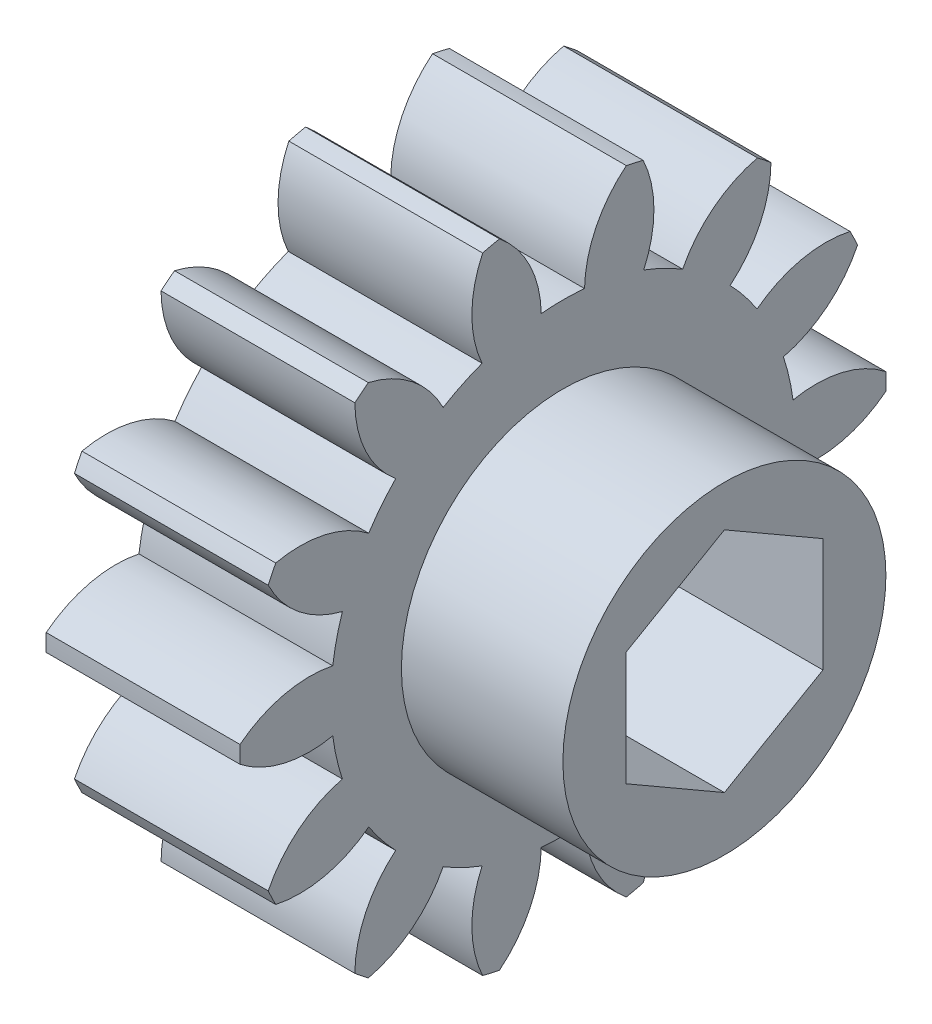
SolidWorks part; units mm, degrees
material "PLA "
ref_plane "Plane1" through (0, 0, 0) normal (0, 0, 1) x (1, 0, 0)
ref_plane "Plane2" through (0, 0, 0) normal (0, 1, 0) x (1, 0, 0)
ref_plane "Plane3" through (0, 0, 0) normal (1, 0, 0) x (0, 0, -1)
sketch "HoldingSke" plane through (0, 0, 0) normal (0, 1, 0) x (1, 0, 0)
  line L0 (0, 0) -> (0.3881, -0.0968)
  line L1 (-15, 0) -> (100, 0) construction
  line L2 (0, 0) -> (-2.1039, 2.3779)
  line L3 (0, 0) -> (-11.863, 4.5341)
  line L4 (0, 0) -> (8.3795, 2.0892)
  line L5 (0, 0) -> (-46.8476, -17.4728)
  line L6 (0, 0) -> (-9.9476, -6.7116)
  line L7 (-2.1039, 2.3779) -> (8.6586, 51.2059)
  line L8 (-76.2, 54.61) -> (-76.1, 54.61)
  line L9 (-71.009, 38.7566) -> (-53.1078, 45.2721)
  line L10 (-76.2, 71.12) -> (104.1128, 71.12)
  line L11 (0, 0) -> (-12, 0)
  line L12 (-76.2, 101.6) -> (-76.113, 101.6)
  line L13 (24.9733, 27.94) -> (52.9518, 28.4284)
  line L14 (24.9733, 27.94) -> (24.9743, 27.94)
  line L15 (24.9733, 27.94) -> (100.4006, 29.5858)
  line L16 (-63.627, -2.5) -> (-12.827, -2.5)
  circle A0 centre (0, 0) radius 0.4
  circle A1 centre (0, 0) radius 14.374
  circle A2 centre (0, 0) radius 37.5
  circle A3 centre (0, 0) radius 0.4
  dimension "MHD" = 28.748
  dimension "Hub_dia" = 75
  dimension "Bore" = 0.8
  dimension "MBD" = 0.8
  dimension "Num_teeth" = 14
  dimension "Pitch" = 0.4
  dimension "Overall_len" = 50
  dimension "Show_teeth" = 14
  dimension "Thickness" = 12
  dimension "OAL" = 50.0001
  dimension "T_dim" = 0.1
  dimension "Ap" = 20
  dimension "H" = 19.05
  dimension "Pitch_radius" = 180.3128
  dimension "Width" = 12
  dimension "Backlash" = 0.087
  dimension "Addendum_fac" = 1
  dimension "Dedendum_fac" = 1.25
  dimension "Clearance_fac" = 0.25
  dimension "Dedendum_add" = 0.001
  dimension "Module" = 2.5
sketch "BasProSke" plane through (0, 0, 0) normal (0, 1, 0) x (1, 0, 0)
  line L0 (-10, 0) -> (60, 0) construction
  line L1 (0, 0) -> (0, 20)
  line L2 (0, 0) -> (12, 0)
  line L3 (12, 0) -> (12, 20)
  line L4 (12, 20) -> (0, 20)
  dimension "Thickness" = 12
  dimension "Diameter" = 40
revolve "Base-Revolve" add sketch "BasProSke" angle 360 about L0
sketch "TooCutSke" plane through (0, 0, 0) normal (1, 0, 0) x (0, 0, -1)
  line L1 (0, 0) -> (0, 107) construction
  line L2 (0, 0) -> (-2.1115, 17.3722) construction
  line L3 (0, 0) -> (-7.7466, 33.9401) construction
  line L4 (-2.1115, 17.3722) -> (-3.8733, 16.97) construction
  arc A0 (1.3395, 14.3115) -> (-1.3395, 14.3115) centre (0, 0) ccw
  arc A1 (3.9542, 19.6311) -> (-3.9542, 19.6311) centre (0, 0) ccw
  circle A2 centre (0, 0) radius 17.5 construction
  circle A3 centre (0, 0) radius 16.4446 construction
  arc A4 (-1.3395, 14.3115) -> (-3.9542, 19.6311) centre (-8.3382, 14.1739) ccw
  arc A5 (3.9542, 19.6311) -> (1.3395, 14.3115) centre (8.3382, 14.1739) ccw
  dimension "Root_dia" = 28.748
  dimension "Overcut_dia" = 40.0508
  dimension "Pitch_dia" = 35
  dimension "Base_dia" = 32.8892
  dimension "Flank_rad" = 7
  dimension "Half_ang" = 12.857
  dimension "Half_CT" = 1.8071
extrude "ToothCut" cut sketch "TooCutSke" along normal through all
fillet "Breaks" [suppressed] radius 0.05
fillet "RootFillets" [suppressed] radius 0.626
pattern_circular "TeethCuts" count 14 every 25.714 about axis through (-10, 0, 0) along (1, 0, 0) of "ToothCut", "RootFillets", "Breaks"
sketch "HubNeaOneSke" plane through (0, 0, 0) normal (-1, 0, 0) x (0, 0, 1)
  circle A0 centre (0, 0) radius 14.374
  dimension "Diameter" = 28.748
extrude "HubNearOne" [suppressed] add sketch "HubNeaOneSke" along normal blind 38.0001
sketch "HubNeaBotSke" plane through (0, 0, 0) normal (-1, 0, 0) x (0, 0, 1)
  circle A0 centre (0, 0) radius 14.374
  dimension "Diameter" = 28.748
extrude "HubNearBoth" [suppressed] add sketch "HubNeaBotSke" along normal blind 19
ref_plane "FarPln" through (12, 0, 0) normal (1, 0, 0) x (0, 0, -1)
sketch "HubFarSke" plane through (12, 0, 0) normal (1, 0, 0) x (0, 0, -1)
  circle A0 centre (0, 0) radius 14.374
  dimension "Diameter" = 28.748
extrude "HubFar" [suppressed] add sketch "HubFarSke" along normal blind 19
sketch "BorSke" plane through (0, 0, 0) normal (1, 0, 0) x (0, 0, -1)
  circle A0 centre (0, 0) radius 0.4
  dimension "Diameter" = 0.8
extrude "Bore" cut sketch "BorSke" along normal mid plane 100.0001
sketch "KeySke" plane through (0, 0, 0) normal (1, 0, 0) x (0, 0, -1)
  line L0 (-0.05, 0) -> (-0.05, 0.5)
  line L1 (-0.05, 0.5) -> (0.05, 0.5)
  line L2 (0.05, 0.5) -> (0.05, 0)
  line L3 (0, 0) -> (0, 34) construction
  line L4 (-0.05, 0) -> (0.05, 0)
  dimension "Offset" = 0.5
  dimension "Width" = 0.1
extrude "Keyway" [suppressed] cut sketch "KeySke" along normal mid plane 100.0001
pattern_circular "Keyway2" [suppressed] count 2 every 90 about axis through (-10, 0, 0) along (1, 0, 0)
sketch "Sketch1" plane through (12, 0, 0) normal (1, 0, 0) x (0, 0, -1)
  circle A0 centre (0, -0.4) radius 10
  circle A1 centre (0, 0) radius 0.4 construction
  dimension "D1" = 20
extrude "Boss-Extrude1" add sketch "Sketch1" along normal blind 10
sketch "Sketch3" plane through (0, 0, 0) normal (0, 0, 1) x (1, 0, 0)
  line L0 (0, 0) -> (6, 0) construction
  dimension "D1" = 6
sketch "Sketch2" plane through (22, 0, 0) normal (1, 0, 0) x (0, 0, -1)
  line L1 (6.1, 3.5218) -> (0, 7.0437)
  line L2 (0, 7.0437) -> (-6.1, 3.5218)
  line L3 (-6.1, 3.5218) -> (-6.1, -3.5218)
  line L4 (-6.1, -3.5218) -> (0, -7.0437)
  line L5 (0, -7.0437) -> (6.1, -3.5218)
  line L6 (6.1, -3.5218) -> (6.1, 3.5218)
  circle A0 centre (0, 0) radius 6.1 construction
  dimension "D1" = 12.2
extrude "Cut-Extrude1" cut sketch "Sketch2" against normal up to vertex
sketch "Sketch4" [suppressed] plane through (5.9116, 0, 0) normal (1, 0, 0) x (0, 0, -1)
  circle A0 centre (0, 0) radius 2.1
  dimension "D1" = 4.2
extrude "Cut-Extrude2" [suppressed] cut sketch "Sketch4" against normal blind 6
equation "' \"Module@HoldingSke\" = 6.35"
equation "' \"Num_teeth@HoldingSke\" = 12"
equation "' \"Ap@HoldingSke\" =  20"
equation "' \"Ap@HoldingSke\" = 20"
equation "' \"Width@HoldingSke\" = 0.5 * 25.4"
equation "' \"Hub_dia@HoldingSke\"= 1 * 25.4"
equation "' \"Hub_dia@HoldingSke\" = 1 * 25.4"
equation "' \"Overall_len@HoldingSke\" = 1.0 * 25.4"
equation "' \"Bore@HoldingSke\" = 0.75 * 25.4"
equation "' \"T_dim@HoldingSke\" = 0.1 * 25.4"
equation "' \"Width@KeySke\" = 0.25 * 25.4"
equation "' \"Show_teeth@HoldingSke\" = 13"
equation "' \"Backlash@HoldingSke\" = 0.009 * 25.4"
equation "' \"Addendum_fac@HoldingSke\" = 1.0"
equation "' \"Dedendum_fac@HoldingSke\" = 1.25"
equation "' \"Dedendum_add@HoldingSke\" = 0.00005 * 25.4"
equation "' \"Clearance_fac@HoldingSke\" = 0.25"
equation "\"Pitch@HoldingSke\" = 1 / \"Module@HoldingSke\""
equation "\"Overcut_dia@TooCutSke\" = (\"Num_teeth@HoldingSke\" + 2 * \"Addendum_fac@HoldingSke\") / \"Pitch@HoldingSke\" + 0.002 * 25.4"
equation "\"Pitch_dia@TooCutSke\" = \"Num_teeth@HoldingSke\" / \"Pitch@HoldingSke\""
equation "\"Base_dia@TooCutSke\" = \"Num_teeth@HoldingSke\" / \"Pitch@HoldingSke\" * cos((\"Ap@HoldingSke\"  * 3.14159265 / 180))"
equation "\"Root_dia@TooCutSke\" = (\"Num_teeth@HoldingSke\" + 2) / \"Pitch@HoldingSke\" - 2 * (\"Addendum_fac@HoldingSke\" + \"Dedendum_fac@HoldingSke\") / \"Pitch@HoldingSke\" - \"Dedendum_add@HoldingSke\" * 2"
equation "\"Half_ang@TooCutSke\" = 180 / \"Num_teeth@HoldingSke\""
equation "\"Half_CT@TooCutSke\" = \"Num_teeth@HoldingSke\" / \"Pitch@HoldingSke\" * sin((3.14159265 / 2 / \"Num_teeth@HoldingSke\")) / 2 - 7 * \"Backlash@HoldingSke\" / 4"
equation "\"Flank_rad@TooCutSke\" = \"Num_teeth@HoldingSke\" / \"Pitch@HoldingSke\" / 5"
equation "\"Radius@RootFillets\" = \"Clearance_fac@HoldingSke\" / \"Pitch@HoldingSke\" + \"Dedendum_add@HoldingSke\""
equation "\"Break_rad@Breaks\" = 0.02 / \"Pitch@HoldingSke\""
equation "\"Thickness@HoldingSke\" = \"Width@HoldingSke\""
equation "\"OAL@HoldingSke\" = \"Thickness@HoldingSke\""
equation "\"MHD@HoldingSke\" = (\"Num_teeth@HoldingSke\" + 2) / \"Pitch@HoldingSke\" - 2 * (\"Addendum_fac@HoldingSke\" + \"Dedendum_fac@HoldingSke\")  / \"Pitch@HoldingSke\" - \"Dedendum_add@HoldingSke\" * 2"
equation "\"MBD@HoldingSke\" = (\"Num_teeth@HoldingSke\" + 2) / \"Pitch@HoldingSke\" - 2 * (\"Addendum_fac@HoldingSke\" + \"Dedendum_fac@HoldingSke\")  / \"Pitch@HoldingSke\" - \"Dedendum_add@HoldingSke\" * 2 - 0.002 * 25.4"
equation "\"MHD@HoldingSke\" = ((sgn( \"MHD@HoldingSke\" - \"Hub_dia@HoldingSke\" )-1)*( \"MHD@HoldingSke\" - \"Hub_dia@HoldingSke\" ))/-2+ \"Hub_dia@HoldingSke\""
equation "\"MBD@HoldingSke\" = ((sgn( \"MBD@HoldingSke\" - \"Bore@HoldingSke\" )-1)*( \"MBD@HoldingSke\" - \"Bore@HoldingSke\" ))/-2+ \"Bore@HoldingSke\""
equation "\"OAL@HoldingSke\" = ((sgn( \"OAL@HoldingSke\" - \"Overall_len@HoldingSke\" )+1)*( \"OAL@HoldingSke\" - \"Overall_len@HoldingSke\" ))/2 + \"Overall_len@HoldingSke\" + 0.000002 * 25.4"
equation "\"Num_teeth@TeethCuts\" = int( \"Show_teeth@HoldingSke\" ) + 1"
equation "\"Num_teeth@TeethCuts\" = ((sgn( \"Num_teeth@TeethCuts\" - \"Num_teeth@HoldingSke\" )-1)*( \"Num_teeth@TeethCuts\" - \"Num_teeth@HoldingSke\" ))/-2+ \"Num_teeth@HoldingSke\""
equation "\"Num_teeth@TeethCuts\" = ((sgn( \"Num_teeth@TeethCuts\" - 2.0)+1)*( \"Num_teeth@TeethCuts\" - 2.0))/2 +2.0"
equation "\"Angle@TeethCuts\" = 360.0 / \"Num_teeth@HoldingSke\""
equation "\"Diameter@BasProSke\" = (\"Num_teeth@HoldingSke\" + 2 * \"Addendum_fac@HoldingSke\") / \"Pitch@HoldingSke\""
equation "\"Thickness@BasProSke\"  = \"Thickness@HoldingSke\""
equation "' \"Fillet_rad@BasProSke\" =  \"Thickness@HoldingSke\" * 0.05"
equation "' \"Fillet_rad@BasProSke\" = \"Thickness@HoldingSke\" * 0.05"
equation "\"MHD@HoldingSke\" = ((sgn( \"MHD@HoldingSke\" - \"Root_dia@TooCutSke\" )-1)*( \"MHD@HoldingSke\" - \"Root_dia@TooCutSke\" ))/-2+ \"Root_dia@TooCutSke\""
equation "\"Diameter@HubNeaOneSke\" = \"MHD@HoldingSke\""
equation "\"Length@HubNearOne\" = \"OAL@HoldingSke\" - \"Thickness@BasProSke\""
equation "\"Diameter@HubNeaBotSke\" = \"MHD@HoldingSke\""
equation "\"Length@HubNearBoth\" = ( \"OAL@HoldingSke\" - \"Thickness@BasProSke\" ) / 2.0"
equation "\"Thickness@FarPln\" = \"Thickness@BasProSke\""
equation "\"Diameter@HubFarSke\" = \"MHD@HoldingSke\""
equation "\"Length@HubFar\" = ( \"OAL@HoldingSke\" - \"Thickness@BasProSke\" ) / 2.0"
equation "\"Diameter@BorSke\" = \"MBD@HoldingSke\""
equation "\"D1@Bore\" = \"OAL@HoldingSke\" * 2.0"
equation "\"D1@Keyway\" = \"OAL@HoldingSke\" * 2.0"
equation "\"Offset@KeySke\" = \"T_dim@HoldingSke\" + \"MBD@HoldingSke\" / 2.0"
